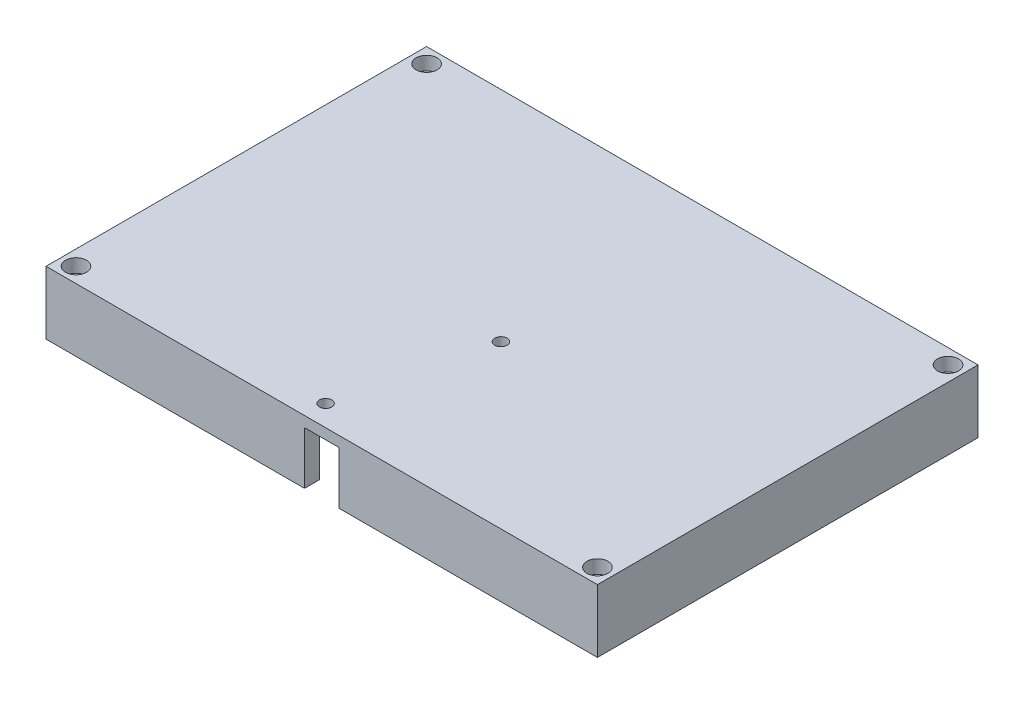
SolidWorks part; units mm, degrees
ref_plane "Front Plane" through (0, 0, 0) normal (0, 0, 1) x (1, 0, 0)
ref_plane "Top Plane" through (0, 0, 0) normal (0, 1, 0) x (1, 0, 0)
ref_plane "Right Plane" through (0, 0, 0) normal (1, 0, 0) x (0, 0, -1)
sketch "Sketch1" plane through (0, 0, 0) normal (0, 1, 0) x (1, 0, 0)
  line L0 (-58.3649, 63.5) -> (-58.3649, -63.5) construction
  line L5 (127, 63.5) -> (-127, 63.5)
  line L6 (127, 63.5) -> (127, -63.5)
  line L7 (127, -63.5) -> (-127, -63.5)
  line L8 (-127, 63.5) -> (-127, -63.5)
  point P0 (0, 0)
  dimension "D1" = 254
  dimension "D2" = 68.6351
  dimension "1" = 127
extrude "Boss-Extrude2" add sketch "Sketch1" along normal blind 19.05
sketch "Sketch2" plane through (0, 0, 0) normal (0, -1, 0) x (1, 0, 0)
  line L12 (-122, 58.5) -> (-122, -58.5)
  line L13 (-122, -58.5) -> (122, -58.5)
  line L14 (122, -58.5) -> (122, 58.5)
  line L15 (122, 58.5) -> (-122, 58.5)
  line L16 (-122, 58.5) -> (-122, -58.5)
  line L17 (-122, -58.5) -> (122, -58.5)
  line L18 (122, -58.5) -> (122, 58.5)
  line L19 (122, 58.5) -> (-122, 58.5)
  dimension "D1" = 5
extrude "Cut-Extrude1" cut sketch "Sketch2" against normal blind 17.05 contours L16 L17 L18 L19
sketch "Sketch4" plane through (0, 19.05, 0) normal (0, 1, 0) x (1, 0, 0)
  line L0 (-57, 63.5) -> (-57, -63.5) construction
  line L1 (127, 63.5) -> (-127, 63.5) construction
  line L2 (-127, -63.5) -> (127, -63.5) construction
  line L3 (-57, 63.5) -> (-57, -63.5)
  line L4 (-57, -63.5) -> (-127, -63.5)
  line L5 (-127, -63.5) -> (-127, 63.5)
  line L6 (-127, 63.5) -> (-127, -63.5) construction
  line L7 (-127, 63.5) -> (-57, 63.5)
  dimension "D1" = 70
sketch "Sketch5" plane through (0, 0, 0) normal (0, -1, 0) x (1, 0, 0)
  line L1 (-127, 63.5) -> (127, 63.5)
  line L2 (-127, 63.5) -> (-127, -63.5)
  line L3 (-127, -63.5) -> (127, -63.5)
  line L4 (127, 63.5) -> (127, -63.5)
extrude "Cut-Extrude2" cut sketch "Sketch4" against normal blind 44
sketch "Sketch6" plane through (0, 17.05, 0) normal (0, -1, 0) x (1, 0, 0)
  line L0 (-57, 58.5) -> (-57, -58.5)
  line L1 (-57, -58.5) -> (-52, -58.5)
  line L2 (-57, -58.5) -> (122, -58.5) construction
  line L3 (-52, -58.5) -> (-52, 58.5)
  line L4 (122, 58.5) -> (-57, 58.5) construction
  line L5 (-52, 58.5) -> (-57, 58.5)
  dimension "D1" = 5
extrude "Boss-Extrude3" add sketch "Sketch6" along normal up to vertex (17.05 mm away)
sketch "Sketch9" plane through (0, 17.05, 0) normal (0, -1, 0) x (1, 0, 0)
  line L4 (122, 58.5) -> (-52, 58.5)
  line L5 (-52, 58.5) -> (-52, -58.5)
  line L6 (-52, -58.5) -> (122, -58.5)
  line L7 (122, -58.5) -> (122, 58.5)
  line L8 (122, 58.5) -> (-52, 58.5)
  line L9 (-52, 58.5) -> (-52, -58.5)
  line L10 (-52, -58.5) -> (122, -58.5)
  line L11 (122, -58.5) -> (122, 58.5)
  dimension "D1" = 0
extrude "Boss-Extrude4" add sketch "Sketch9" along normal blind 4
sketch "Sketch12" plane through (0, 0, 0) normal (0, -1, 0) x (1, 0, 0)
  line L0 (39.25, 58.5) -> (30.75, 58.5)
  line L1 (122, 58.5) -> (-52, 58.5) construction
  line L2 (30.75, 58.5) -> (30.75, 63.5)
  line L3 (-127, 63.5) -> (127, 63.5) construction
  line L4 (30.75, 63.5) -> (39.25, 63.5)
  line L5 (39.25, 63.5) -> (39.25, 58.5)
  point P5 (35, 58.5)
  dimension "D1" = 8.5
extrude "Cut-Extrude3" cut sketch "Sketch12" against normal up to vertex (13.05 mm away)
sketch "Sketch13" plane through (0, 13.05, 0) normal (0, -1, 0) x (1, 0, 0)
  line L0 (30.75, 58.5) -> (39.25, 58.5) construction
  line L1 (24.45, 58.5) -> (45.55, 58.5)
  line L2 (122, 58.5) -> (39.25, 58.5) construction
  line L3 (24.45, 58.5) -> (24.45, 7.4)
  line L4 (24.45, 7.4) -> (45.55, 7.4)
  line L5 (45.55, 7.4) -> (45.55, 58.5)
  line L6 (30.75, 58.5) -> (30.75, 54)
  line L7 (30.75, 54) -> (39.25, 54)
  line L8 (39.25, 54) -> (39.25, 58.5)
  line L9 (30.75, 58.5) -> (39.25, 58.5)
  point P9 (35, 58.5)
  line M6 (122, 58.5) -> (39.25, 58.5)
  line M10 (30.75, 58.5) -> (-52, 58.5)
  dimension "D1" = 21.1
  dimension "D2" = 51.1
sketch "Sketch14" plane through (0, 0, 0) normal (0, -1, 0) x (1, 0, 0)
  line L0 (29.2686, 58.5) -> (40.7314, 58.5)
  line L1 (24.45, 58.5) -> (45.55, 58.5) construction
  line L2 (29.2686, 58.5) -> (29.2686, 63.5) construction
  line L3 (-127, 63.5) -> (127, 63.5) construction
  line L4 (29.2686, 63.5) -> (40.7314, 63.5) construction
  line L5 (40.7314, 63.5) -> (40.7314, 58.5) construction
  line L6 (29.2686, 63.5) -> (40.7314, 63.5)
  line L7 (40.7314, 63.5) -> (40.7314, 58.5)
  line L8 (29.2686, 58.5) -> (29.2686, 63.5)
  point P6 (35, 58.5)
  dimension "D1" = 11.4628
extrude "Cut-Extrude4" cut sketch "Sketch13" against normal blind 1 contours L8 L7 L6 L3 L4 L5 M10 M6
sketch "Sketch15" plane through (0, 13.05, 0) normal (0, -1, 0) x (1, 0, 0)
  line L6 (30.75, 54) -> (39.25, 54)
  line L7 (39.25, 54) -> (39.25, 58.5)
  line L8 (39.25, 58.5) -> (39.25, 63.5)
  line L9 (39.25, 63.5) -> (30.75, 63.5)
  line L10 (30.75, 63.5) -> (30.75, 58.5)
  line L11 (30.75, 58.5) -> (30.75, 54)
  line L12 (30.75, 54) -> (39.25, 54)
  line L13 (39.25, 54) -> (39.25, 58.5)
  line L14 (39.25, 58.5) -> (39.25, 63.5)
  line L15 (39.25, 63.5) -> (30.75, 63.5)
  line L16 (30.75, 63.5) -> (30.75, 58.5)
  line L17 (30.75, 58.5) -> (30.75, 54)
  dimension "D1" = 0
extrude "Cut-Extrude5" cut sketch "Sketch15" against normal blind 4.5
sketch "Sketch17" plane through (0, 14.05, 0) normal (0, -1, 0) x (1, 0, 0)
  line L0 (24.45, 58.5) -> (26.65, 58.5)
  line L1 (30.75, 58.5) -> (-52, 58.5) construction
  line L2 (26.65, 58.5) -> (26.65, 7.4)
  line L3 (24.45, 7.4) -> (45.55, 7.4) construction
  line L4 (26.65, 7.4) -> (24.45, 7.4)
  line L5 (24.45, 7.4) -> (24.45, 58.5)
  line L6 (45.55, 58.5) -> (43.35, 58.5)
  line L7 (45.55, 58.5) -> (39.25, 58.5) construction
  line L8 (45.55, 58.5) -> (45.55, 7.4)
  line L9 (45.55, 7.4) -> (43.35, 7.4)
  line L10 (24.45, 7.4) -> (45.55, 7.4) construction
  line L11 (43.35, 7.4) -> (43.35, 58.5)
  dimension "D1" = 2.2
extrude "Cut-Extrude6" cut sketch "Sketch17" against normal blind 1.5
sketch "Sketch18" plane through (0, 0, 0) normal (0, -1, 0) x (1, 0, 0)
  circle A0 centre (-52, 58.5) radius 3.5
  circle A1 centre (122, 58.5) radius 3.5
  circle A2 centre (122, -58.5) radius 3.5
  circle A3 centre (-52, -58.5) radius 3.5
  dimension "D1" = 7
  dimension "D2" = 7
  dimension "D3" = 7
  dimension "D4" = 7
sketch "Sketch19" plane through (0, 14.05, 0) normal (0, -1, 0) x (1, 0, 0)
  line L0 (26.65, 58.5) -> (26.65, 43.5) construction
  line L1 (26.65, 7.4) -> (26.65, 58.5) construction
  line L2 (26.65, 43.5) -> (34.05, 43.5)
  line L3 (34.05, 43.5) -> (34.05, 49.5)
  line L4 (34.05, 49.5) -> (26.65, 49.5)
  line L5 (26.65, 49.5) -> (26.65, 43.5)
  dimension "D1" = 7.4
extrude "Cut-Extrude7" cut sketch "Sketch19" against normal blind 4
sketch "Sketch20" plane through (0, 19.05, 0) normal (0, 1, 0) x (1, 0, 0)
  circle A0 centre (-52, -58.5) radius 3.5 construction
  circle A1 centre (122, -58.5) radius 3.5 construction
  circle A2 centre (122, 58.5) radius 3.5 construction
  circle A3 centre (-52, 58.5) radius 3.5 construction
  circle A4 centre (-52, -58.5) radius 3.5
  circle A5 centre (122, -58.5) radius 3.5
  circle A6 centre (122, 58.5) radius 3.5
  circle A7 centre (-52, 58.5) radius 3.5
extrude "Cut-Extrude8" cut sketch "Sketch20" against normal blind 2.5
sketch "Sketch23" plane through (0, 16.55, 0) normal (0, 1, 0) x (1, 0, 0)
  circle A0 centre (-52, 58.5) radius 1.5
  circle A1 centre (-52, -58.5) radius 1.5
  circle A2 centre (122, -58.5) radius 1.5
  circle A3 centre (122, 58.5) radius 1.5
  dimension "D1" = 3
  dimension "D2" = 3
  dimension "D3" = 3
  dimension "D4" = 3
extrude "Cut-Extrude9" cut sketch "Sketch23" against normal blind 38
sketch "Sketch24" plane through (0, 13.05, 0) normal (0, -1, 0) x (1, 0, 0)
  line L0 (-52, 57) -> (-52, 55)
  line L1 (-52, 57) -> (-52, -57) construction
  line L2 (-48.5, -58.5) -> (-50.5, -58.5)
  line L3 (-52, -57) -> (-52, -55)
  line L4 (-48.5, 58.5) -> (-50.5, 58.5)
  line L5 (120.5, 58.5) -> (39.25, 58.5) construction
  line L6 (122, -57) -> (122, 57) construction
  line L7 (122, 55) -> (122, 57)
  line L8 (118.5, 58.5) -> (120.5, 58.5)
  line L9 (-50.5, -58.5) -> (120.5, -58.5) construction
  line L10 (122, -57) -> (122, -55)
  line L11 (120.5, -58.5) -> (118.5, -58.5)
  arc A0 (-52, -57) -> (-50.5, -58.5) centre (-52, -58.5) cw
  arc A1 (-50.5, -58.5) -> (-52, -57) centre (-52, -58.5) ccw construction
  arc A2 (-52, -55) -> (-48.5, -58.5) centre (-52, -58.5) cw
  circle A3 centre (-52, -58.5) radius 3.5 construction
  arc A4 (-52, 57) -> (-50.5, 58.5) centre (-52, 58.5) ccw
  arc A5 (-52, 57) -> (-50.5, 58.5) centre (-52, 58.5) ccw construction
  arc A6 (-52, 55) -> (-48.5, 58.5) centre (-52, 58.5) ccw
  circle A7 centre (-52, 58.5) radius 3.5 construction
  arc A8 (120.5, 58.5) -> (122, 57) centre (122, 58.5) ccw
  arc A9 (120.5, 58.5) -> (122, 57) centre (122, 58.5) ccw construction
  arc A10 (118.5, 58.5) -> (122, 55) centre (122, 58.5) ccw
  circle A11 centre (122, 58.5) radius 3.5 construction
  arc A12 (120.5, -58.5) -> (122, -57) centre (122, -58.5) cw
  arc A13 (118.5, -58.5) -> (122, -55) centre (122, -58.5) cw
  circle A14 centre (122, -58.5) radius 3.5 construction
extrude "Boss-Extrude5" add sketch "Sketch24" along normal up to surface (13.05 mm away) up to face at (35, 0, 15.25)
sketch "Sketch25" plane through (0, 14.05, 0) normal (0, -1, 0) x (1, 0, 0)
  line L0 (34.05, 43.5) -> (43.35, 43.5)
  line L1 (43.35, 58.5) -> (43.35, 7.4) construction
  line L2 (34.05, 49.5) -> (43.35, 49.5)
  line L3 (43.35, 49.5) -> (43.35, 43.5)
  line L4 (34.05, 49.5) -> (34.05, 43.5)
extrude "Cut-Extrude10" cut sketch "Sketch25" against normal up to surface (4 mm away) up to face at (30.35, 18.05, 46.5)
sketch "Sketch26" plane through (0, 14.05, 0) normal (0, -1, 0) x (1, 0, 0)
  line L0 (30.75, 54) -> (30.75, 52.1093)
  line L1 (39.25, 54) -> (39.25, 52.1093)
  line L2 (39.25, 52.1093) -> (30.75, 52.1093)
  line L3 (30.75, 54) -> (39.25, 54)
extrude "Cut-Extrude11" cut sketch "Sketch26" against normal up to surface (3.5 mm away) up to face at (35, 17.55, 58.75)
sketch "Sketch27" plane through (0, 14.05, 0) normal (0, -1, 0) x (1, 0, 0)
  line L0 (45.55, 7.4) -> (45.55, 58.5) construction
  line L1 (24.45, 7.4) -> (45.55, 7.4) construction
  line L2 (24.45, 58.5) -> (24.45, 7.4) construction
  line L3 (30.75, 58.5) -> (-48.5, 58.5) construction
  circle A0 centre (40.7, 9.4) radius 0.95
  circle A1 centre (29.3, 56.5) radius 0.95
  dimension "D3" = 1.9
  dimension "D5" = 2
  dimension "D6" = 1.9
  dimension "D1" = 4.85
  dimension "D2" = 2
  dimension "D4" = 4.85
extrude "Cut-Extrude13" cut sketch "Sketch27" against normal blind 25
sketch "Sketch28" plane through (0, 19.05, 0) normal (0, 1, 0) x (1, 0, 0)
  circle A0 centre (40.7, -9.4) radius 2.06
  circle A1 centre (29.3, -56.5) radius 2.06
  dimension "D1" = 4.12
  dimension "D2" = 4.12
extrude "Cut-Extrude18" cut sketch "Sketch28" against normal blind 1.24
sketch "Sketch31" plane through (0, 19.05, 0) normal (0, 1, 0) x (1, 0, 0)
  line L4 (127, 63.5) -> (-57, 63.5)
  line L5 (-57, 63.5) -> (-57, -63.5)
  line L6 (-57, -63.5) -> (127, -63.5)
  line L7 (127, -63.5) -> (127, 63.5)
  line L8 (127, 63.5) -> (-57, 63.5)
  line L9 (-57, 63.5) -> (-57, -63.5)
  line L10 (-57, -63.5) -> (127, -63.5)
  line L11 (127, -63.5) -> (127, 63.5)
  circle A0 centre (-52, 58.5) radius 3.5 construction
  circle A1 centre (40.7, -9.4) radius 2.06
  circle A2 centre (40.7, -9.4) radius 2.06
  circle A3 centre (-52, -58.5) radius 3.5 construction
  circle A4 centre (29.3, -56.5) radius 2.06 construction
  circle A5 centre (122, -58.5) radius 3.5 construction
  circle A6 centre (122, 58.5) radius 3.5 construction
  circle A7 centre (-52, 58.5) radius 3.5
  circle A8 centre (-52, -58.5) radius 3.5
  circle A9 centre (29.3, -56.5) radius 2.06
  circle A10 centre (122, -58.5) radius 3.5
  circle A11 centre (122, 58.5) radius 3.5
  dimension "D1" = 0
  dimension "D2" = 0
extrude "Boss-Extrude6" add sketch "Sketch31" along normal blind 2
extrude "Cut-Extrude19" cut sketch "Sketch14" against normal up to surface (17.55 mm away) contours L0 L7 L6 L8 up to face at (35, 17.55, 57.8046)
